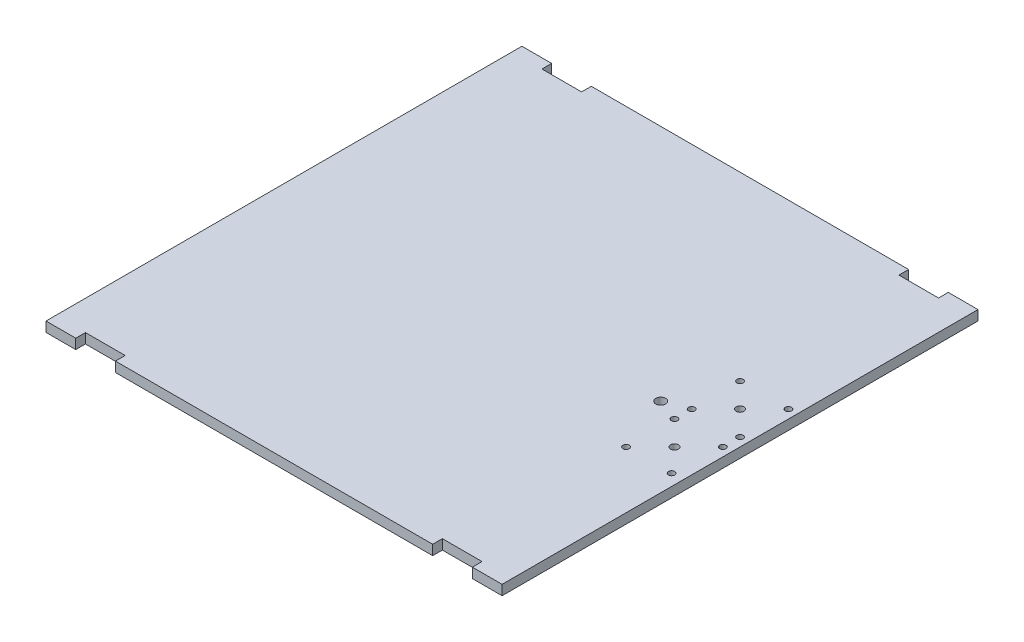
SolidWorks part; units mm, degrees
ref_plane "Front Plane" through (0, 0, 0) normal (0, 0, 1) x (1, 0, 0)
ref_plane "Top Plane" through (0, 0, 0) normal (0, 1, 0) x (1, 0, 0)
ref_plane "Right Plane" through (0, 0, 0) normal (1, 0, 0) x (0, 0, -1)
sketch "Sketch1" plane through (0, 0, 0) normal (0, 1, 0) x (1, 0, 0)
  line L0 (292.1, 152.4) -> (0, 152.4) construction
  line L2 (0, 0) -> (0, 304.8)
  line L3 (0, 304.8) -> (292.1, 304.8)
  line L4 (292.1, 0) -> (292.1, 304.8)
  line L5 (12.7, 12.7) -> (228.6, 12.7)
  line L6 (12.7, 12.7) -> (12.7, 292.1)
  line L7 (12.7, 292.1) -> (228.6, 292.1)
  line L8 (228.6, 12.7) -> (228.6, 292.1)
  line L13 (247.65, 0) -> (273.05, 0)
  line L14 (247.65, 0) -> (247.65, 6.223)
  line L15 (247.65, 6.223) -> (273.05, 6.223)
  line L16 (273.05, 0) -> (273.05, 6.223)
  line L17 (247.65, 298.577) -> (273.05, 298.577)
  line L18 (273.05, 304.8) -> (273.05, 298.577)
  line L19 (247.65, 304.8) -> (273.05, 304.8)
  line L20 (247.65, 304.8) -> (247.65, 298.577)
  line L25 (0, 0) -> (292.1, 0)
  point P9 (12.7, 152.4)
  point P10 (0, 152.4)
  dimension "D1" = 304.8
  dimension "D2" = 279.4
  dimension "D4" = 12.7
  dimension "D5" = 292.1
  dimension "D6" = 25.4
  dimension "D7" = 6.223
  dimension "D8" = 19.05
extrude "Boss-Extrude1" add sketch "Sketch1" along normal blind 6.35
sketch "Sketch2" [suppressed] plane through (0, 6.35, 0) normal (0, 1, 0) x (1, 0, 0)
  line L0 (0, 0) -> (247.65, 0) construction
  line L1 (0, 304.8) -> (228.6, 304.8)
  line L2 (0, 304.8) -> (0, 0)
  line L3 (0, 0) -> (228.6, 0)
  line L4 (228.6, 304.8) -> (228.6, 0)
  line L5 (292.1, 0) -> (292.1, 304.8) construction
  dimension "D1" = 63.5
extrude "Cut-Extrude1" [suppressed] cut sketch "Sketch2" against normal blind 9.525
sketch "Sketch3" [suppressed] plane through (0, 6.35, 0) normal (0, 1, 0) x (1, 0, 0)
  line L0 (241.3, 171.45) -> (241.3, 133.35) construction
  line L1 (241.3, 203.2) -> (247.523, 203.2)
  line L2 (241.3, 203.2) -> (241.3, 171.45)
  line L3 (241.3, 171.45) -> (247.523, 171.45)
  line L4 (247.523, 203.2) -> (247.523, 171.45)
  line L5 (241.3, 133.35) -> (247.523, 133.35)
  line L6 (241.3, 133.35) -> (241.3, 101.6)
  line L7 (241.3, 101.6) -> (247.523, 101.6)
  line L8 (247.523, 133.35) -> (247.523, 101.6)
  line L9 (228.6, 0) -> (228.6, 304.8) construction
  line L11 (260.35, 172.7) -> (280.35, 172.7)
  line L12 (260.35, 172.7) -> (260.35, 132.1)
  line L13 (260.35, 132.1) -> (280.35, 132.1)
  line L14 (280.35, 172.7) -> (280.35, 132.1)
  line L15 (265.35, 176.7) -> (275.35, 176.7) construction
  line L16 (275.35, 176.7) -> (275.35, 128.1) construction
  line L17 (275.35, 128.1) -> (265.35, 128.1) construction
  line L18 (265.35, 128.1) -> (265.35, 176.7) construction
  circle A0 centre (275.35, 176.7) radius 2
  circle A1 centre (265.35, 176.7) radius 2
  circle A2 centre (265.35, 128.1) radius 2
  circle A3 centre (275.35, 128.1) radius 2
  point P10 (228.6, 152.4)
  point P11 (241.3, 152.4)
  point P16 (260.35, 152.4)
  point P25 (275.35, 152.4)
  point P26 (280.35, 152.4)
  point P27 (270.35, 172.7)
  point P28 (270.35, 176.7)
  dimension "D8" = 4
  dimension "D1" = 31.75
  dimension "D2" = 6.223
  dimension "D3" = 38.1
  dimension "D4" = 12.7
  dimension "D5" = 40.6
  dimension "D6" = 20
  dimension "D7" = 31.75
  dimension "D9" = 10
  dimension "D10" = 48.6
extrude "Cut-Extrude2" [suppressed] cut sketch "Sketch3" against normal blind 9.525
sketch "Sketch4" plane through (0, 6.35, 0) normal (0, 1, 0) x (1, 0, 0)
  line L0 (292.1, 0) -> (292.1, 304.8) construction
  line L1 (286.6, 188.9) -> (255.6, 188.9) construction
  line L2 (286.6, 188.9) -> (286.6, 157.9) construction
  line L3 (286.6, 157.9) -> (255.6, 157.9) construction
  line L4 (255.6, 188.9) -> (255.6, 157.9) construction
  line L5 (286.6, 146.9) -> (255.6, 146.9) construction
  line L6 (286.6, 146.9) -> (286.6, 115.9) construction
  line L7 (286.6, 115.9) -> (255.6, 115.9) construction
  line L8 (255.6, 146.9) -> (255.6, 115.9) construction
  line L9 (286.6, 157.9) -> (286.6, 146.9) construction
  line L10 (146.05, 304.8) -> (146.05, 0) construction
  line L11 (247.65, 304.8) -> (273.05, 304.8)
  line L12 (247.65, 304.8) -> (247.65, 298.577)
  line L13 (247.65, 298.577) -> (273.05, 298.577)
  line L14 (273.05, 304.8) -> (273.05, 298.577)
  line L15 (273.05, 6.223) -> (247.65, 6.223)
  line L16 (273.05, 6.223) -> (273.05, 0)
  line L17 (273.05, 0) -> (247.65, 0)
  line L18 (247.65, 6.223) -> (247.65, 0)
  line L19 (0, 304.8) -> (247.65, 304.8) construction
  line L20 (0, 0) -> (247.65, 0) construction
  line L23 (19.05, 0) -> (44.45, 0)
  line L24 (44.45, 6.223) -> (44.45, 0)
  line L25 (19.05, 6.223) -> (44.45, 6.223)
  line L26 (19.05, 6.223) -> (19.05, 0)
  line L27 (44.45, 298.577) -> (19.05, 298.577)
  line L28 (19.05, 304.8) -> (19.05, 298.577)
  line L29 (44.45, 304.8) -> (19.05, 304.8)
  line L30 (44.45, 304.8) -> (44.45, 298.577)
  circle A0 centre (286.6, 188.9) radius 2
  circle A1 centre (286.6, 157.9) radius 2
  circle A2 centre (255.6, 157.9) radius 2
  circle A3 centre (255.6, 188.9) radius 2
  circle A4 centre (255.6, 146.9) radius 2
  circle A5 centre (286.6, 146.9) radius 2
  circle A6 centre (284.7635, 115.9) radius 2
  circle A7 centre (255.6, 115.9) radius 2
  circle A9 centre (271.1, 173.4) radius 2.5
  circle A10 centre (271.1, 131.4) radius 2.5
  circle A11 centre (241.3, 152.4) radius 3.175
  point P10 (286.6, 152.4)
  point P11 (292.1, 152.4)
  point P23 (286.6, 173.4)
  point P46 (0, 0)
  point P47 (286.6, 131.4)
  dimension "D5" = 4
  dimension "D6" = 6.35
  dimension "D7" = 5
  dimension "D1" = 31
  dimension "D2" = 5.5
  dimension "D3" = 5.5
  dimension "D4" = 11
  dimension "D8" = 146.05
  dimension "D9" = 50.8
extrude "Cut-Extrude3" cut sketch "Sketch4" against normal through all
sketch "Sketch5" plane through (0, 6.35, 0) normal (0, 1, 0) x (1, 0, 0)
  line L1 (228.6, 292.1) -> (12.7, 292.1)
  line L2 (228.6, 292.1) -> (228.6, 12.7)
  line L3 (228.6, 12.7) -> (12.7, 12.7)
  line L4 (12.7, 292.1) -> (12.7, 12.7)
extrude "Boss-Extrude2" add sketch "Sketch5" against normal up to surface (6.35 mm away) up to face at (241.3, 0, -149.225)
